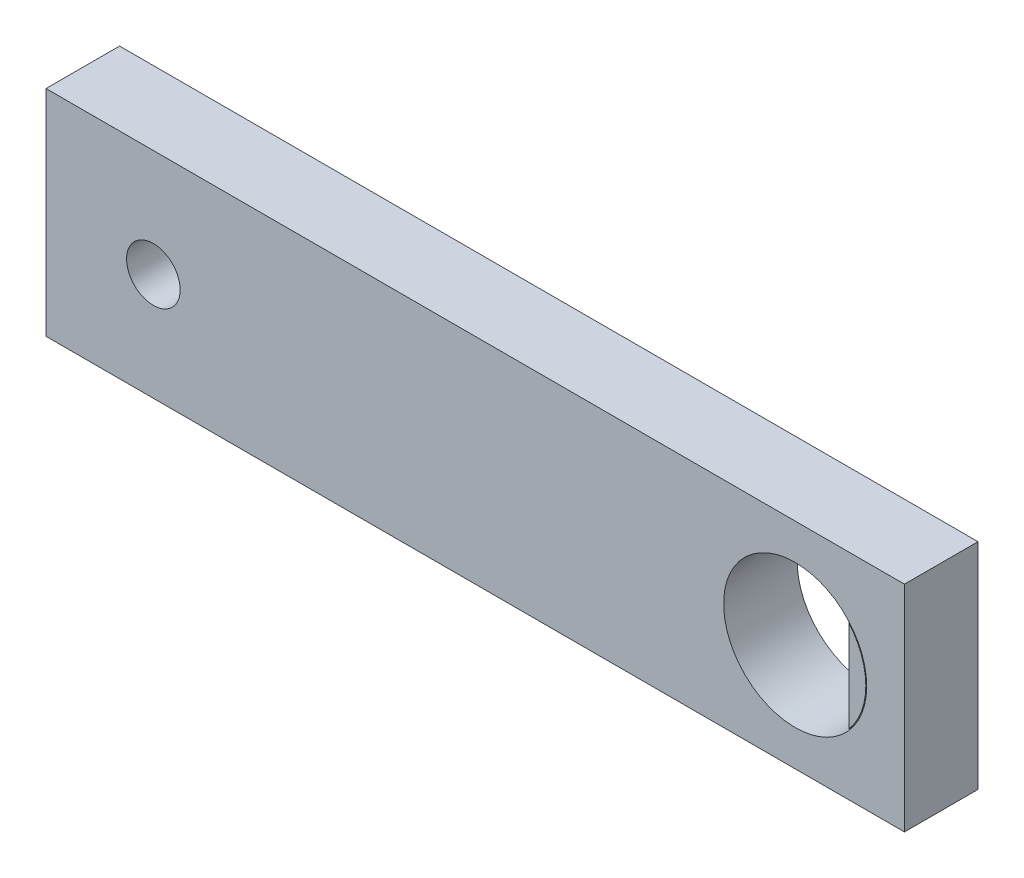
SolidWorks part; units mm, degrees
ref_plane "Front Plane" through (0, 0, 0) normal (0, 0, 1) x (1, 0, 0)
ref_plane "Top Plane" through (0, 0, 0) normal (0, 1, 0) x (1, 0, 0)
ref_plane "Right Plane" through (0, 0, 0) normal (1, 0, 0) x (0, 0, -1)
sketch "Sketch1" plane through (0, 0, 0) normal (0, 0, 1) x (1, 0, 0)
  line L1 (-38.1, -9.525) -> (38.1, -9.525)
  line L2 (-38.1, -9.525) -> (-38.1, 9.525)
  line L3 (-38.1, 9.525) -> (38.1, 9.525)
  line L4 (38.1, -9.525) -> (38.1, 9.525)
  line L5 (-38.1, -9.525) -> (38.1, 9.525) construction
  line L6 (-38.1, 9.525) -> (38.1, -9.525) construction
  circle A0 centre (-28.57, 0) radius 2.38
  circle A1 centre (28.4, 0) radius 6.35
  point P0 (0, 0)
  dimension "D5" = 4.76
  dimension "D6" = 12.7
  dimension "D1" = 76.2
  dimension "D2" = 19.05
  dimension "D3" = 9.7
  dimension "D4" = 9.53
extrude "Boss-Extrude1" add sketch "Sketch1" along normal blind 6.53
sketch "Sketch2" plane through (0, 0, 6.53) normal (0, 0, 1) x (1, 0, 0)
  line L0 (33.16, 4.0839) -> (33.16, -4.0839)
  circle A0 centre (28.4, 0) radius 6.2718
  dimension "D1" = 4.76
extrude "Boss-Extrude2" add sketch "Sketch2" against normal blind 6.35 separate body contours L0 A0
